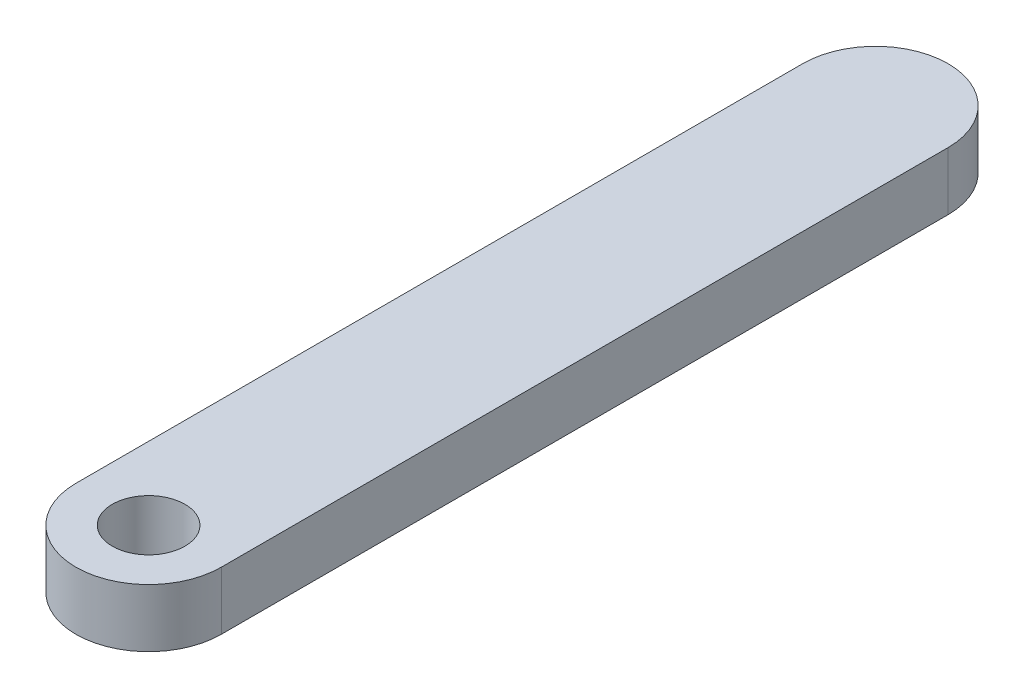
SolidWorks part; units mm, degrees
material "ABS"
ref_plane "正面" through (0, 0, 0) normal (0, 0, 1) x (1, 0, 0)
ref_plane "平面" through (0, 0, 0) normal (0, 1, 0) x (1, 0, 0)
ref_plane "右側面" through (0, 0, 0) normal (1, 0, 0) x (0, 0, -1)
sketch "ｽｹｯﾁ1" plane through (0, 0, 0) normal (0, 1, 0) x (1, 0, 0)
  line L0 (-10, 0) -> (-10, 100)
  line L1 (10, 100) -> (10, 0)
  arc A0 (-10, 100) -> (10, 100) centre (0, 100) cw
  arc A1 (10, 0) -> (-10, 0) centre (0, 0) cw
  circle A2 centre (0, 0) radius 5
extrude "ﾎﾞｽ - 押し出し1" add sketch "ｽｹｯﾁ1" along normal blind 8
